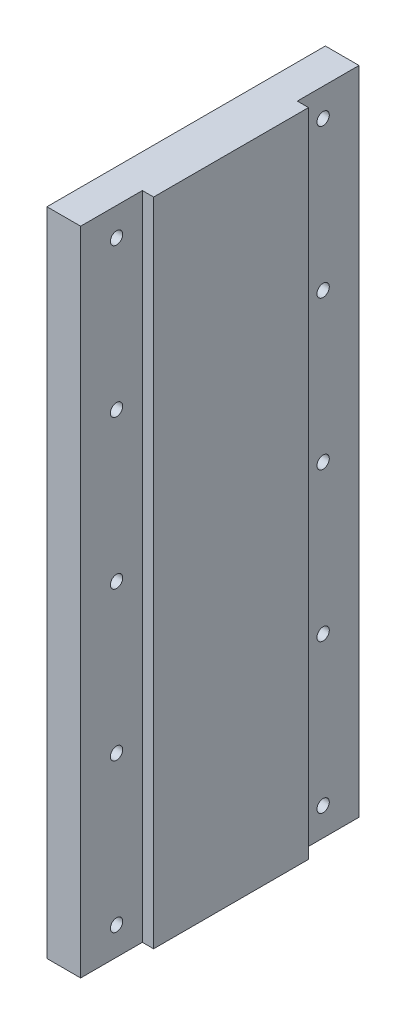
SolidWorks part; units mm, degrees
ref_plane "Front Plane" through (0, 0, 0) normal (0, 0, 1) x (1, 0, 0)
ref_plane "Top Plane" through (0, 0, 0) normal (0, 1, 0) x (1, 0, 0)
ref_plane "Right Plane" through (0, 0, 0) normal (1, 0, 0) x (0, 0, -1)
sketch "Sketch1" plane through (0, 0, 0) normal (0, 1, 0) x (1, 0, 0)
  line L0 (0, 0) -> (0, -248)
  line L1 (0, -248) -> (30, -248)
  line L2 (30, -248) -> (30, -193)
  line L3 (30, -193) -> (40, -193)
  line L4 (40, -193) -> (40, -55)
  line L5 (40, -55) -> (30, -55)
  line L6 (30, -55) -> (30, 0)
  line L7 (30, 0) -> (0, 0)
extrude "Boss-Extrude1" add sketch "Sketch1" along normal blind 580
sketch "Sketch2" plane through (30, 0, 0) normal (1, 0, 0) x (0, 0, -1)
  line L0 (-55, 0) -> (0, 0) construction
  line L2 (-124, 0) -> (-124, 150.8483) construction
  line L3 (-193, 0) -> (-55, 0) construction
  circle A0 centre (-32, 25) radius 5.5
  dimension "D1" = 11
  dimension "D3" = 92
  dimension "D2" = 25
extrude "Cut-Extrude1" cut sketch "Sketch2" against normal up to next
chamfer "Chamfer1" distance 6 angle 45 1 edges at (0, 25, 26.5)
pattern_linear "LPattern1" count 5 spacing 132.5 along (0, 1, 0) count 2 spacing 184 along (0, 0, 1) of "Cut-Extrude1", "Chamfer1"
